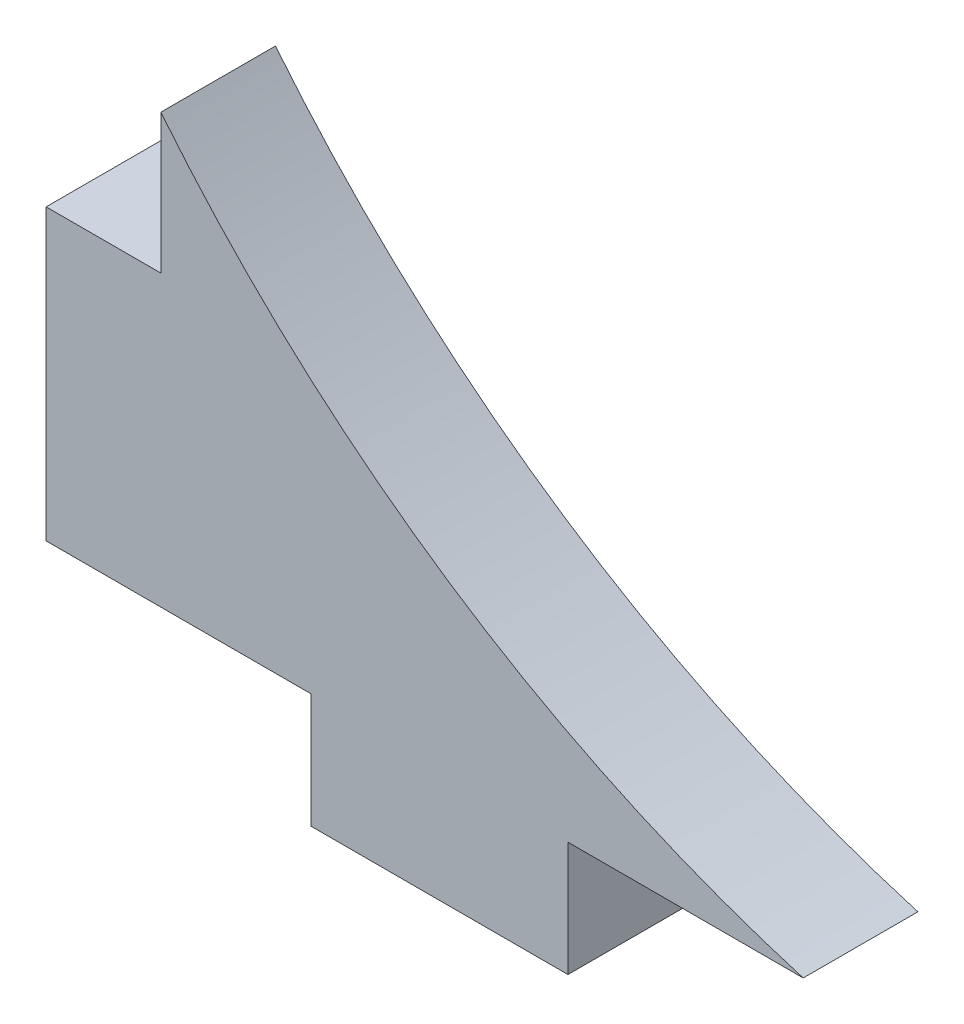
SolidWorks part; units mm, degrees
ref_plane "Front Plane" through (0, 0, 0) normal (0, 0, 1) x (1, 0, 0)
ref_plane "Top Plane" through (0, 0, 0) normal (0, 1, 0) x (1, 0, 0)
ref_plane "Right Plane" through (0, 0, 0) normal (1, 0, 0) x (0, 0, -1)
sketch "Model" plane through (0, 0, 0) normal (0, 0, 1) x (1, 0, 0)
  line L388 (5.35, 18.85) -> (5.35, 25.35)
  line L389 (0, 18.85) -> (5.35, 18.85)
  line L390 (0, 5.35) -> (0, 18.85)
  line L391 (12.35, 5.35) -> (0, 5.35)
  line L392 (12.35, 0) -> (12.35, 5.35)
  line L393 (24.35, 0) -> (12.35, 0)
  line L394 (24.35, 5.35) -> (24.35, 0)
  line L395 (35.3281, 5.35) -> (24.35, 5.35)
  arc A55 (5.35, 25.35) -> (35.3281, 5.35) centre (52.4119, 63.4242) ccw
extrude "Boss-Extrude1" add sketch "Model" along normal blind 5.35
